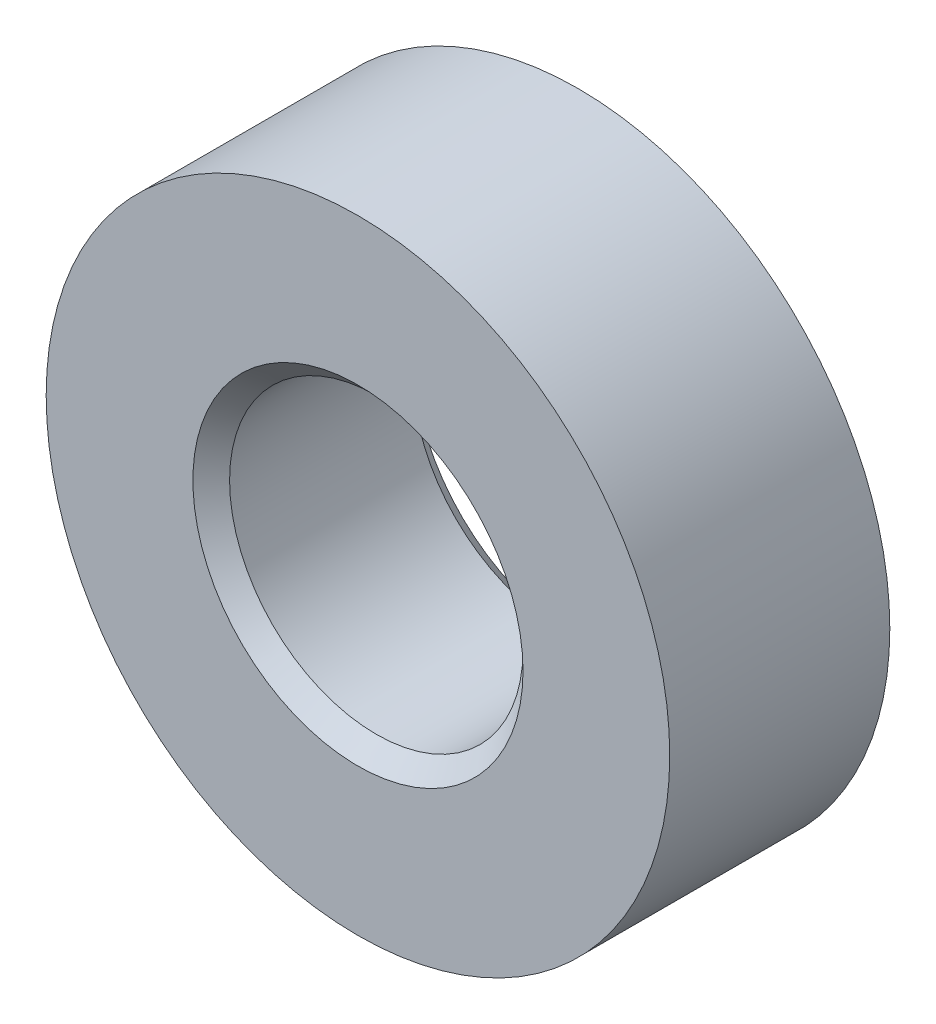
SolidWorks part; units mm, degrees
ref_plane "Front Plane" through (0, 0, 0) normal (0, 0, 1) x (1, 0, 0)
ref_plane "Top Plane" through (0, 0, 0) normal (0, 1, 0) x (1, 0, 0)
ref_plane "Right Plane" through (0, 0, 0) normal (1, 0, 0) x (0, 0, -1)
sketch "Sketch1" plane through (0, 0, 0) normal (0, 0, 1) x (1, 0, 0)
  circle A0 centre (0, 0) radius 8.5
  circle A1 centre (0, 0) radius 4
  dimension "D1" = 8
  dimension "D2" = 17
extrude "Boss-Extrude1" add sketch "Sketch1" along normal blind 6
chamfer "Chamfer1" distance 0.5 angle 45 2 edges at (4, 0, 0) (4, 0, 6)
